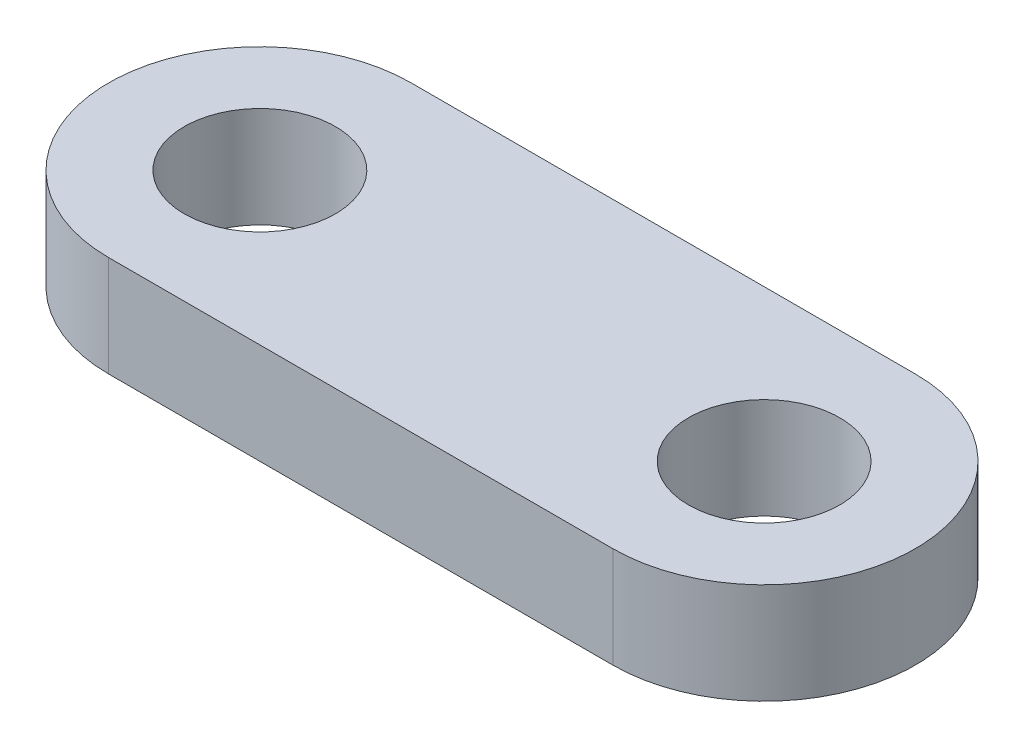
SolidWorks part; units mm, degrees
ref_plane "前视基准面" through (0, 0, 0) normal (0, 0, 1) x (1, 0, 0)
ref_plane "上视基准面" through (0, 0, 0) normal (0, 1, 0) x (1, 0, 0)
ref_plane "右视基准面" through (0, 0, 0) normal (1, 0, 0) x (0, 0, -1)
sketch "草图1" plane through (0, 0, 0) normal (0, 1, 0) x (1, 0, 0)
  line L0 (-5, 0) -> (5, 0) construction
  line L1 (-5, 3) -> (5, 3)
  line L2 (-5, -3) -> (5, -3)
  arc A0 (-5, 3) -> (-5, -3) centre (-5, 0) ccw
  arc A1 (5, -3) -> (5, 3) centre (5, 0) ccw
  circle A2 centre (-5, 0) radius 1.5
  circle A3 centre (5, 0) radius 1.5
  point P2 (0, 0)
  dimension "D2" = 3
  dimension "D3" = 3
  dimension "D1" = 10
extrude "凸台-拉伸1" add sketch "草图1" along normal mid plane 2
